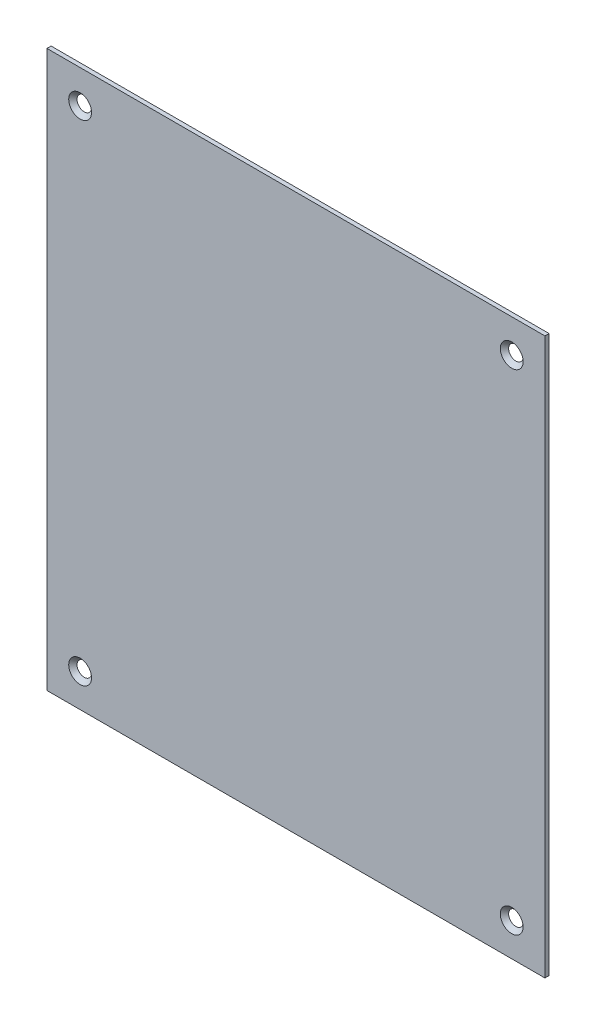
SolidWorks part; units mm, degrees
ref_plane "Front Plane" through (0, 0, 0) normal (0, 0, 1) x (1, 0, 0)
ref_plane "Top Plane" through (0, 0, 0) normal (0, 1, 0) x (1, 0, 0)
ref_plane "Right Plane" through (0, 0, 0) normal (1, 0, 0) x (0, 0, -1)
sketch "Sketch1" plane through (0, 0, 0) normal (0, 0, 1) x (1, 0, 0)
  line L1 (-71.134, 57.9897) -> (48.866, 57.9897)
  line L2 (-71.134, 57.9897) -> (-71.134, -76.0103)
  line L3 (-71.134, -76.0103) -> (48.866, -76.0103)
  line L4 (48.866, 57.9897) -> (48.866, -76.0103)
  dimension "D1" = 120
  dimension "D2" = 134
extrude "Boss-Extrude2" add sketch "Sketch1" against normal blind 1
hole_wizard "CSK for M2.5 Countersunk Flat Head1" positions "Sketch3" profile "Sketch4" countersink size "M2.5" standard "BSI"
sketch "Sketch3" plane through (0, 0, 0) normal (0, 0, 1) x (1, 0, 0)
  line L0 (48.866, -76.0103) -> (48.866, 57.9897) construction
  line L1 (48.866, 57.9897) -> (-71.134, 57.9897) construction
  line L2 (-71.134, -76.0103) -> (48.866, -76.0103) construction
  line L3 (-71.134, 57.9897) -> (-71.134, -76.0103) construction
  point P0 (-63.134, 49.9897)
  point P2 (-63.134, -68.0103)
  point P4 (40.866, -68.0103)
  point P6 (40.866, 49.9897)
  dimension "D1" = 8
  dimension "D2" = 8
  dimension "D3" = 8
  dimension "D4" = 8
  dimension "D5" = 8
  dimension "D6" = 8
  dimension "D7" = 8
  dimension "D8" = 8
sketch "Sketch4" plane through (-63.134, 49.9897, 0) normal (1, 0, 0) x (0, -1, 0)
  line L0 (0, 0) -> (0, 1.8712)
  line L1 (0, 1.8712) -> (1.45, 1)
  line L2 (1.45, 1) -> (1.45, 1.3)
  line L3 (1.45, 1.3) -> (2.75, 0)
  line L5 (2.75, 0) -> (0, 0)
  line L6 (-1.45, 1.3) -> (-2.75, 0) construction
  line L10 (0, 1.8712) -> (-1.45, 1) construction
  line L11 (0, -6.35) -> (0, 107.95) construction
  dimension "Hole Dia." = 2.9
  dimension "Hole Depth" = 1
  dimension "Near C'Sink Dia." = 5.5
  dimension "Near C'Sink Angle" = 90
  dimension "Drill Angle" = 118
